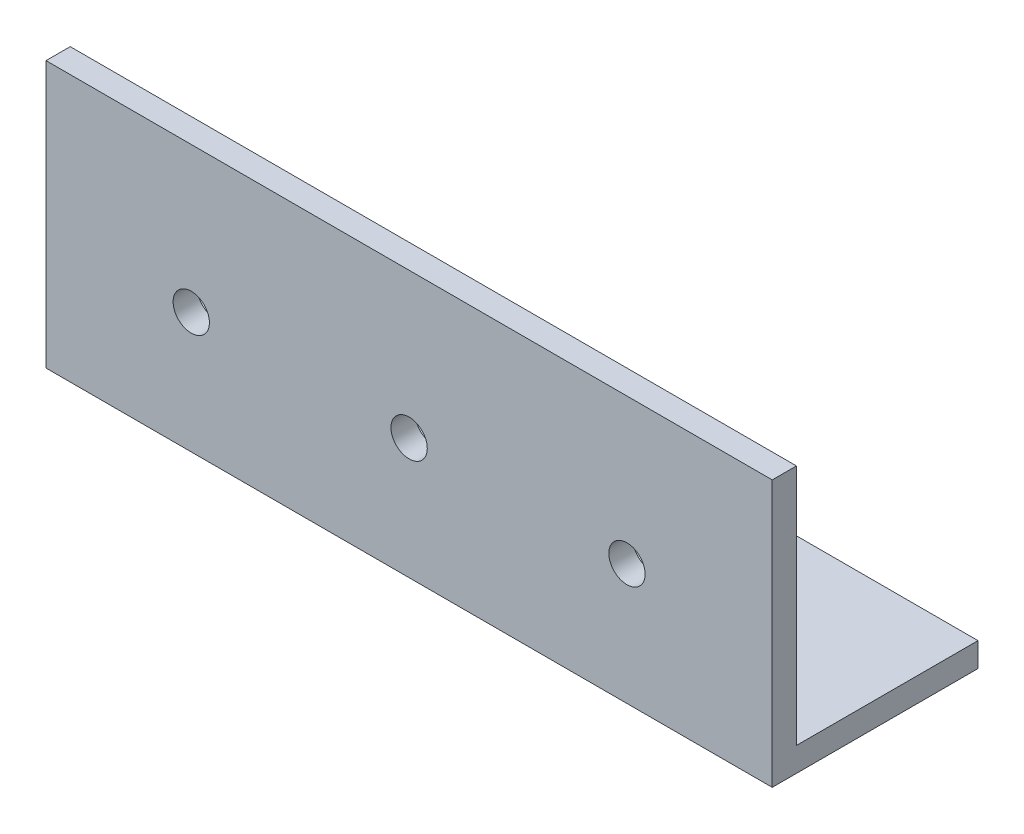
SolidWorks part; units mm, degrees
ref_plane "Front Plane" through (0, 0, 0) normal (0, 0, 1) x (1, 0, 0)
ref_plane "Top Plane" through (0, 0, 0) normal (0, 1, 0) x (1, 0, 0)
ref_plane "Right Plane" through (0, 0, 0) normal (1, 0, 0) x (0, 0, -1)
sketch "Sketch1" plane through (0, 0, 0) normal (1, 0, 0) x (0, 0, -1)
  line L0 (0, 0) -> (0, 22)
  line L1 (0, 22) -> (2, 22)
  line L2 (2, 22) -> (2, 2)
  line L3 (2, 2) -> (17, 2)
  line L4 (17, 2) -> (17, 0)
  line L5 (17, 0) -> (0, 0)
  dimension "D1" = 22
  dimension "D2" = 2
  dimension "D3" = 17
  dimension "D4" = 2
extrude "Boss-Extrude1" add sketch "Sketch1" along normal blind 60
sketch "Sketch2" plane through (0, 0, 0) normal (0, -1, 0) x (1, 0, 0)
  line L0 (0, -8.5) -> (60, -8.5) construction
  line L1 (0, 0) -> (0, -17) construction
  line L2 (60, 0) -> (60, -17) construction
  circle A0 centre (30, -8.5) radius 1.5
  circle A1 centre (12, -8.5) radius 1.5
  circle A2 centre (48, -8.5) radius 1.5
  dimension "D1" = 3
  dimension "D2" = 18
  dimension "D3" = 18
extrude "Cut-Extrude1" cut sketch "Sketch2" against normal blind 10
sketch "Sketch3" plane through (0, 0, 0) normal (0, 0, 1) x (1, 0, 0)
  line L0 (0, 10) -> (60, 10) construction
  line L1 (0, 22) -> (0, 0) construction
  line L2 (60, 22) -> (60, 0) construction
  line L3 (60, 0) -> (0, 0) construction
  circle A0 centre (30, 10) radius 1.5
  circle A1 centre (12, 10) radius 1.5
  circle A2 centre (48, 10) radius 1.5
  dimension "D2" = 3
  dimension "D3" = 18
  dimension "D1" = 10
  dimension "D4" = 18
extrude "Cut-Extrude2" cut sketch "Sketch3" against normal blind 10
